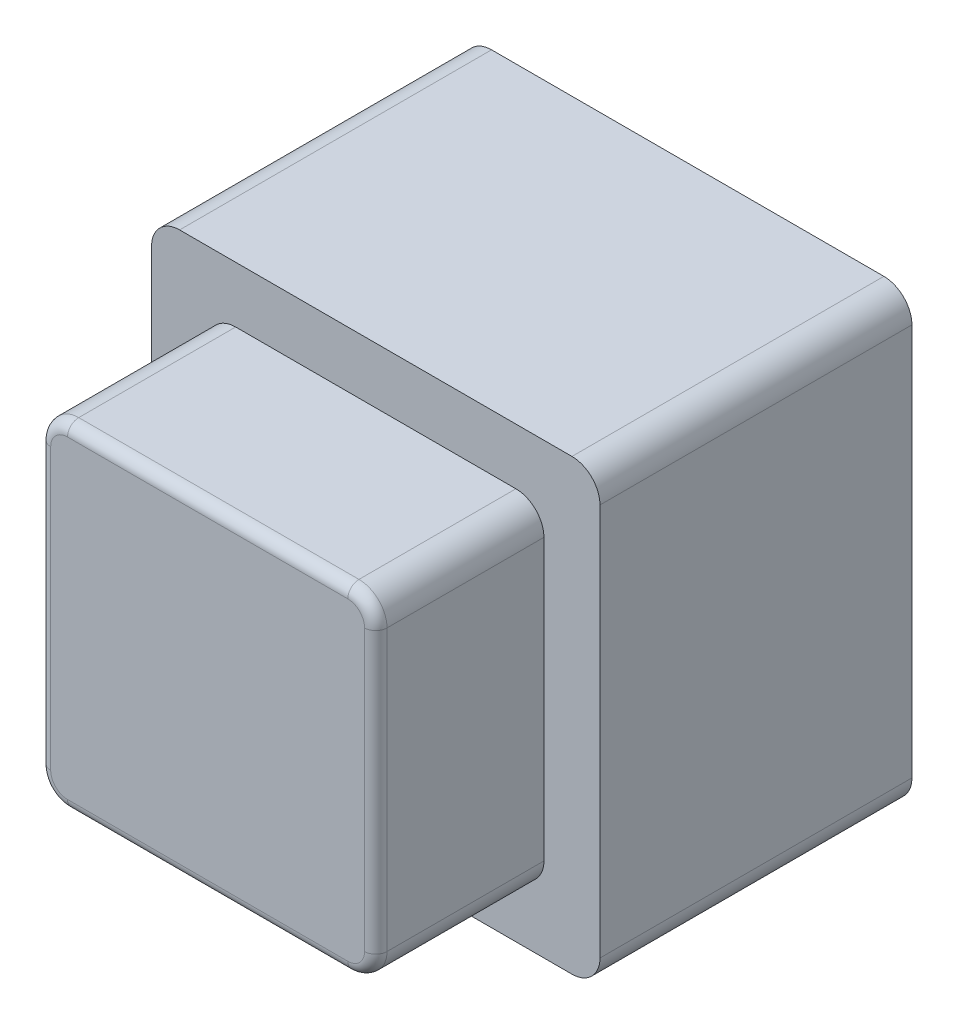
SolidWorks part; units mm, degrees
material "Plastique personnalisé"
ref_plane "Plan de face" through (0, 0, 0) normal (0, 0, 1) x (1, 0, 0)
ref_plane "Plan de dessus" through (0, 0, 0) normal (0, 1, 0) x (1, 0, 0)
ref_plane "Plan de droite" through (0, 0, 0) normal (1, 0, 0) x (0, 0, -1)
sketch "Esquisse1" plane through (0, 0, 0) normal (0, 0, 1) x (1, 0, 0)
  line L1 (-2.5, -3) -> (2.5, -3)
  line L2 (-3, -2.5) -> (-3, 2.5)
  line L3 (-2.5, 3) -> (2.5, 3)
  line L4 (3, -2.5) -> (3, 2.5)
  line L5 (-3, -3) -> (3, 3) construction
  line L6 (-3, 3) -> (3, -3) construction
  arc A0 (-2.5, -3) -> (-3, -2.5) centre (-2.5, -2.5) cw
  arc A1 (2.5, -3) -> (3, -2.5) centre (2.5, -2.5) ccw
  arc A2 (-3, 2.5) -> (-2.5, 3) centre (-2.5, 2.5) cw
  arc A3 (2.5, 3) -> (3, 2.5) centre (2.5, 2.5) cw
  point P0 (0, 0)
  dimension "D3" = 0.5
  dimension "D1" = 6
  dimension "D2" = 6
extrude "Boss.-Extru.1" add sketch "Esquisse1" along normal blind 3
fillet "Congé1" radius 0.2 8 edges at (3, 0, 3) (2.8536, -2.8536, 3) (0, -3, 3) (-2.8536, -2.8536, 3) (-3, 0, 3) (-2.8536, 2.8536, 3) (0, 3, 3) (2.8536, 2.8536, 3)
sketch "Esquisse2" plane through (0, 0, 0) normal (0, 0, 1) x (1, 0, 0)
  line L1 (-3.5, -4) -> (3.5, -4)
  line L2 (-4, -3.5) -> (-4, 3.5)
  line L3 (-3.5, 4) -> (3.5, 4)
  line L4 (4, -3.5) -> (4, 3.5)
  line L5 (-4, -4) -> (4, 4) construction
  line L6 (-4, 4) -> (4, -4) construction
  arc A0 (-3.5, -4) -> (-4, -3.5) centre (-3.5, -3.5) cw
  arc A1 (3.5, -4) -> (4, -3.5) centre (3.5, -3.5) ccw
  arc A2 (-4, 3.5) -> (-3.5, 4) centre (-3.5, 3.5) cw
  arc A3 (3.5, 4) -> (4, 3.5) centre (3.5, 3.5) cw
  point P0 (0, 0)
  dimension "D3" = 0.5
  dimension "D1" = 8
  dimension "D2" = 8
extrude "Boss.-Extru.2" add sketch "Esquisse2" against normal up to surface (5.5654 mm away)
